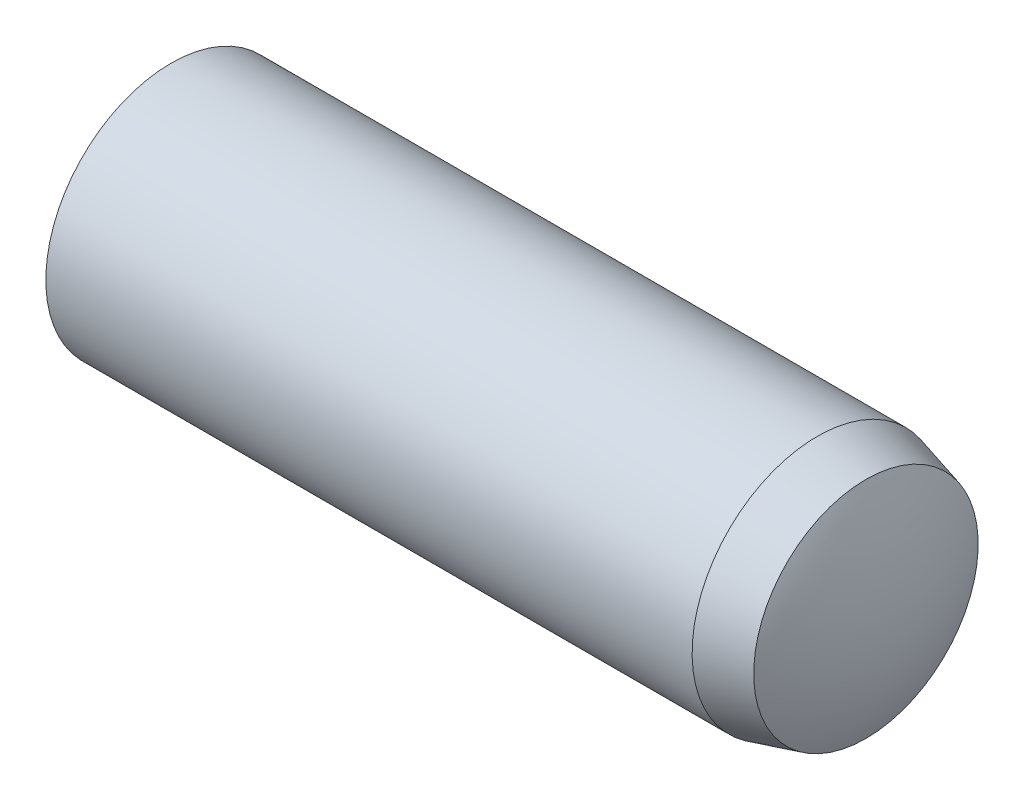
SolidWorks part; units mm, degrees
ref_plane "Plane1" through (0, 0, 0) normal (0, 0, 1) x (1, 0, 0)
ref_plane "Plane2" through (0, 0, 0) normal (0, 1, 0) x (1, 0, 0)
ref_plane "Plane3" through (0, 0, 0) normal (1, 0, 0) x (0, 0, -1)
sketch "BodySke" plane through (0, 0, 0) normal (0, 0, 1) x (1, 0, 0)
  line L0 (0, 0) -> (40.9091, 0) construction
  line L1 (27, 5) -> (28.9403, 4.4801)
  line L2 (1.2, 5) -> (27, 5)
  line L4 (0, 0) -> (30, 0)
  arc A0 (1.2, 5) -> (0, 0) centre (11.0167, 0) ccw
  arc A1 (30, 0) -> (28.9403, 4.4801) centre (20, 0) ccw
  dimension "TipRad" = 10
  dimension "D1" = 15
  dimension "Diameter" = 10
  dimension "Crown_ht" = 1.2
  dimension "Length" = 30
  dimension "Chamfer_len" = 3
revolve "Body" add sketch "BodySke" angle 360 about L0
equation "\"TipRad@BodySke\" = \"Diameter@BodySke\""
